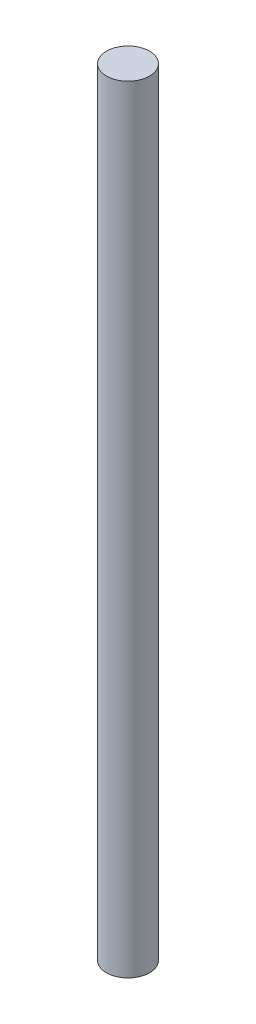
SolidWorks part; units mm, degrees
ref_plane "Front Plane" through (0, 0, 0) normal (0, 0, 1) x (1, 0, 0)
ref_plane "Top Plane" through (0, 0, 0) normal (0, 1, 0) x (1, 0, 0)
ref_plane "Right Plane" through (0, 0, 0) normal (1, 0, 0) x (0, 0, -1)
sketch "Sketch2" plane through (0, 0, 0) normal (0, 1, 0) x (1, 0, 0)
  circle A0 centre (0, 0) radius 5
extrude "Boss-Extrude1" add sketch "Sketch2" along normal blind 180
